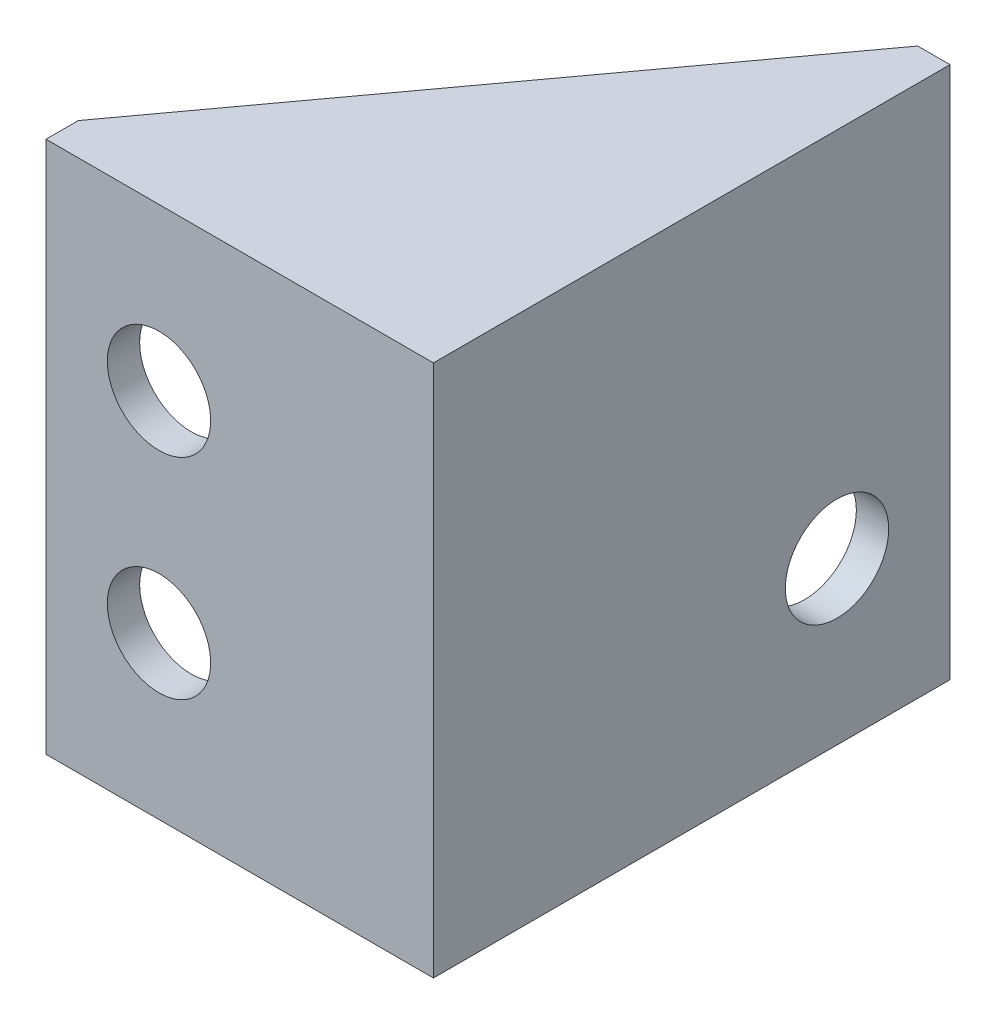
SolidWorks part; units mm, degrees
ref_plane "前视基准面" through (0, 0, 0) normal (0, 0, 1) x (1, 0, 0)
ref_plane "上视基准面" through (0, 0, 0) normal (0, 1, 0) x (1, 0, 0)
ref_plane "右视基准面" through (0, 0, 0) normal (1, 0, 0) x (0, 0, -1)
sketch "草图1" plane through (0, 0, 0) normal (0, 1, 0) x (1, 0, 0)
  line L0 (0, 0) -> (12, 0)
  line L1 (12, 0) -> (12, 16)
  line L2 (12, 16) -> (11, 16)
  line L3 (11, 16) -> (11, 1)
  line L4 (11, 1) -> (0, 1)
  line L5 (0, 1) -> (0, 0)
  dimension "D1" = 12
  dimension "D2" = 1
  dimension "D3" = 1
  dimension "D4" = 16
extrude "凸台-拉伸1" add sketch "草图1" along normal blind 16.5
sketch "草图2" plane through (12, 0, 0) normal (1, 0, 0) x (0, 0, -1)
  line L0 (0, 0) -> (16, 0) construction
  line L2 (0, 5) -> (7.0901, 5) construction
  line L3 (16, 16.5) -> (16, 0) construction
  circle A0 centre (12.5, 5) radius 1.6
  dimension "D1" = 3.2
  dimension "D2" = 5
  dimension "D3" = 3.5
extrude "切除-拉伸1" cut sketch "草图2" against normal blind 6
sketch "草图3" plane through (0, 0, -1) normal (0, 0, -1) x (-1, 0, 0)
  line L1 (0, 16.5) -> (0, 0) construction
  line L2 (-12, 8.25) -> (4.8779, 8.25) construction
  line L3 (-12, 16.5) -> (-12, 0) construction
  circle A0 centre (-3.5, 5) radius 1.6
  circle A1 centre (-3.5, 11.5) radius 1.6
  dimension "D2" = 3.2
  dimension "D1" = 3.5
  dimension "D4" = 6.5
extrude "切除-拉伸2" cut sketch "草图3" against normal blind 10
sketch "草图4" plane through (0, 0, 0) normal (0, -1, 0) x (1, 0, 0)
  line L0 (0, -1) -> (11, -1)
  line L1 (11, -1) -> (11, -16)
  line L2 (11, -16) -> (0, -1)
extrude "凸台-拉伸2" add sketch "草图4" against normal blind 1
sketch "草图5" plane through (0, 16.5, 0) normal (0, 1, 0) x (1, 0, 0)
  line L0 (0, 1) -> (11, 1)
  line L1 (11, 1) -> (11, 16)
  line L2 (11, 16) -> (0, 1)
extrude "凸台-拉伸3" add sketch "草图5" against normal blind 1
